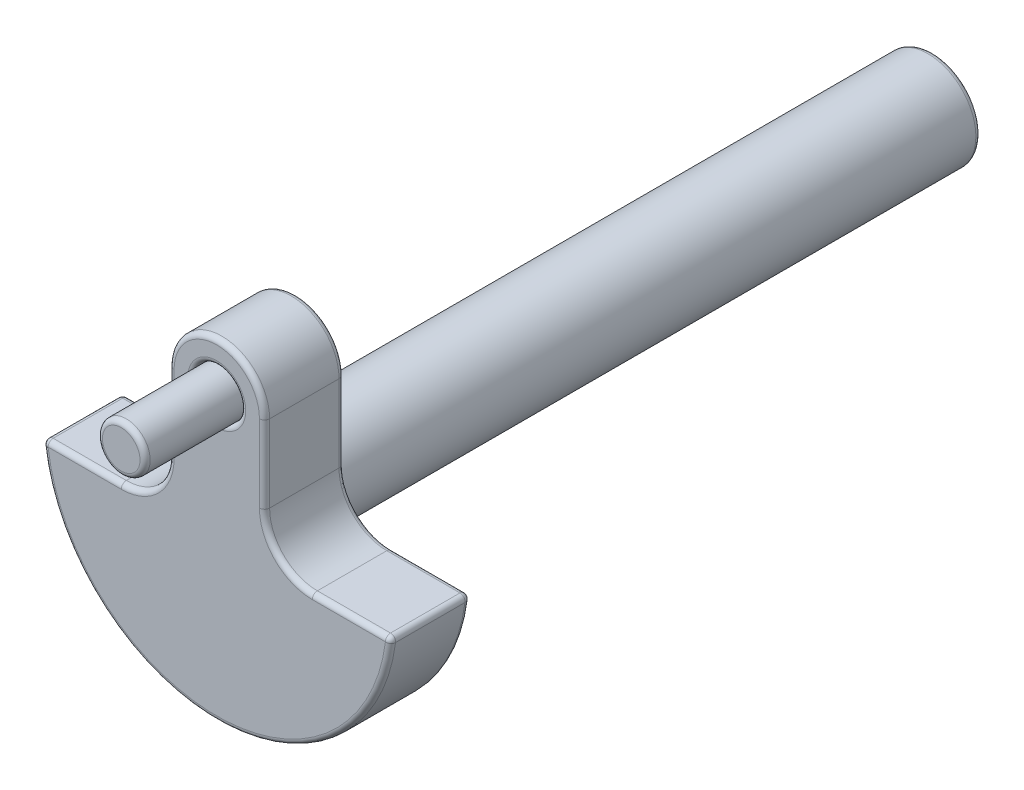
SolidWorks part; units mm, degrees
material "AISI 1015 Steel, Cold Drawn (SS)"
ref_plane "Front Plane" through (0, 0, 0) normal (0, 0, 1) x (1, 0, 0)
ref_plane "Top Plane" through (0, 0, 0) normal (0, 1, 0) x (1, 0, 0)
ref_plane "Right Plane" through (0, 0, 0) normal (1, 0, 0) x (0, 0, -1)
sketch "Sketch1" plane through (0, 0, 0) normal (0, 0, 1) x (1, 0, 0)
  line L0 (-2.3813, 5.4186) -> (-2.3813, 1.5647)
  line L1 (-4.7625, -0.8165) -> (-8.693, -0.8165)
  line L2 (0, 5.4186) -> (0, -0.9314) construction
  line L3 (4.7625, -0.8165) -> (8.693, -0.8165)
  line L4 (2.3813, 5.4186) -> (2.3813, 1.5647)
  arc A0 (-8.693, -0.8165) -> (8.693, -0.8165) centre (0, 0) ccw
  arc A1 (2.3813, 5.4186) -> (-2.3813, 5.4186) centre (0, 5.4186) ccw
  arc A2 (4.7625, -0.8165) -> (2.3813, 1.5647) centre (4.7625, 1.5647) cw
  arc A3 (-2.3813, 1.5647) -> (-4.7625, -0.8165) centre (-4.7625, 1.5647) cw
  point P12 (2.3813, -0.8165)
  point P15 (-2.3812, -0.8165)
  dimension "D1" = 8.7312
  dimension "D2" = 2.3813
  dimension "D4" = 2.3813
  dimension "D3" = 6.35
extrude "Boss-Extrude1" add sketch "Sketch1" against normal blind 3.9688
sketch "Sketch2" plane through (0, 0, 0) normal (0, 0, 1) x (1, 0, 0)
  circle A0 centre (0, 0) radius 1.9844
  circle A1 centre (0, 5.4186) radius 1.1906
  arc A2 (2.3813, 5.4186) -> (-2.3813, 5.4186) centre (0, 5.4186) ccw construction
  dimension "D1" = 2.3813
  dimension "D2" = 3.9688
extrude "Cut-Extrude1" cut sketch "Sketch2" against normal through all
sketch "Sketch3" plane through (0, 0, 0) normal (0, 0, 1) x (1, 0, 0)
  circle A0 centre (0, 5.4186) radius 1.1906 construction
  circle A1 centre (0, 5.4186) radius 1.1906
extrude "Boss-Extrude2" add sketch "Sketch3" along normal blind 4.7625 and the other way up to surface (3.9688 mm away) separate body other way up to face at (1.9844, 0, -3.9688)
sketch "Sketch4" plane through (0, 0, 0) normal (1, 0, 0) x (0, 0, -1)
  line L0 (0, 0) -> (35.7188, 0) construction
  line L1 (35.7188, 0) -> (35.7188, 2.3813)
  line L2 (35.7188, 2.3813) -> (3.9688, 2.3812)
  line L3 (3.9688, 1.5647) -> (3.9688, 5.4186) construction
  line L4 (3.9688, 2.3812) -> (3.9688, 1.9844)
  line L5 (3.9688, 1.9844) -> (0, 1.9844)
  line L6 (0, 1.9844) -> (0, 0)
  line L7 (0, 0) -> (35.7188, 0)
  dimension "D1" = 4.7625
  dimension "D2" = 31.75
revolve "Revolve1" add sketch "Sketch4" angle 360 about L0
fillet "Fillet1" radius 0.254 4 edges at (1.1906, 5.4186, 0) (1.1906, 5.4186, -3.9688) (-8.693, -0.8165, -1.9844) (8.693, -0.8165, -1.9844)
fillet "Fillet3" radius 0.254 20 edges at (3.0787, -0.1191, -3.9688) (6.5859, -0.8165, -3.9688) (8.6, -0.9026, -3.9688) (0, -8.7312, -3.9688) (-8.6, -0.9026, -3.9688) (-6.5859, -0.8165, -3.9688) (-3.0787, -0.1191, -3.9688) (-2.3813, 3.4917, -3.9688) (0, 7.7999, -3.9688) (-3.0787, -0.1191, 0) (-2.3813, 3.4917, 0) (0, 7.7999, 0) (2.3813, 3.4917, 0) (3.0787, -0.1191, 0) (6.5859, -0.8165, 0) (8.6, -0.9026, 0) (0, -8.7312, 0) (-8.6, -0.9026, 0) (-6.5859, -0.8165, 0) (2.3813, 3.4917, -3.9688)
fillet "Fillet4" radius 0.254 2 edges at (1.1906, 5.4186, 4.7625) (-1.1906, 5.4186, -3.9688)
fillet "Fillet5" radius 0.254 1 edges at (2.3813, 0, -35.7188)
